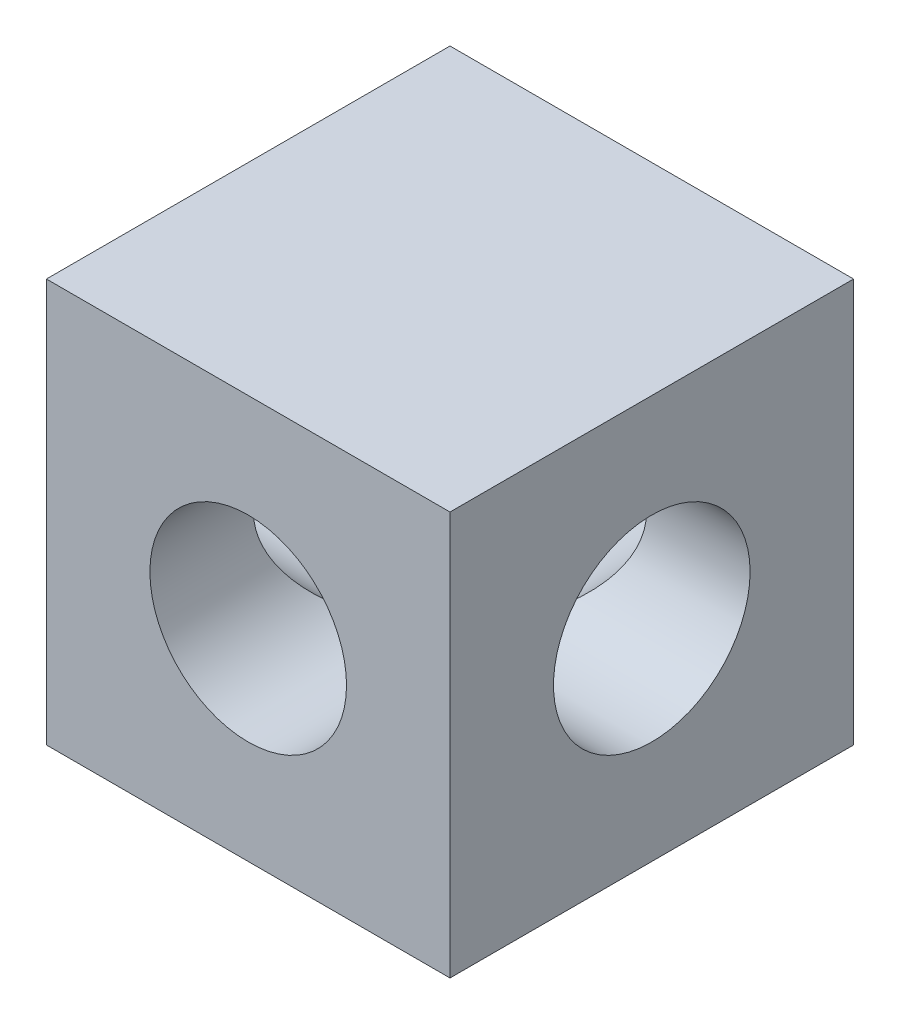
SolidWorks part; units mm, degrees
ref_plane "Front" through (0, 0, 0) normal (0, 0, 1) x (1, 0, 0)
ref_plane "Top" through (0, 0, 0) normal (0, 1, 0) x (-1, 0, 0)
ref_plane "Right" through (0, 0, 0) normal (1, 0, 0) x (0, 0, -1)
sketch "Sketch1" plane through (0, 0, 0) normal (0, 0, 1) x (1, 0, 0)
  line L0 (-9.75, -9.75) -> (9.75, -9.75)
  line L1 (-9.75, -9.75) -> (-9.75, 9.75)
  line L2 (9.75, 9.75) -> (-9.75, 9.75)
  line L3 (9.75, 9.75) -> (9.75, -9.75)
  line L4 (9.75, 9.75) -> (-9.75, -9.75) construction
  circle A0 centre (0, 0) radius 4.75
extrude "Base-Extrude" add sketch "Sketch1" along normal mid plane 19.5
sketch "Sketch3" plane through (9.75, 0, 0) normal (1, 0, 0) x (0, 0, -1)
  circle A0 centre (0, 0) radius 4.75
extrude "Cut-Extrude1" cut sketch "Sketch3" against normal through all
